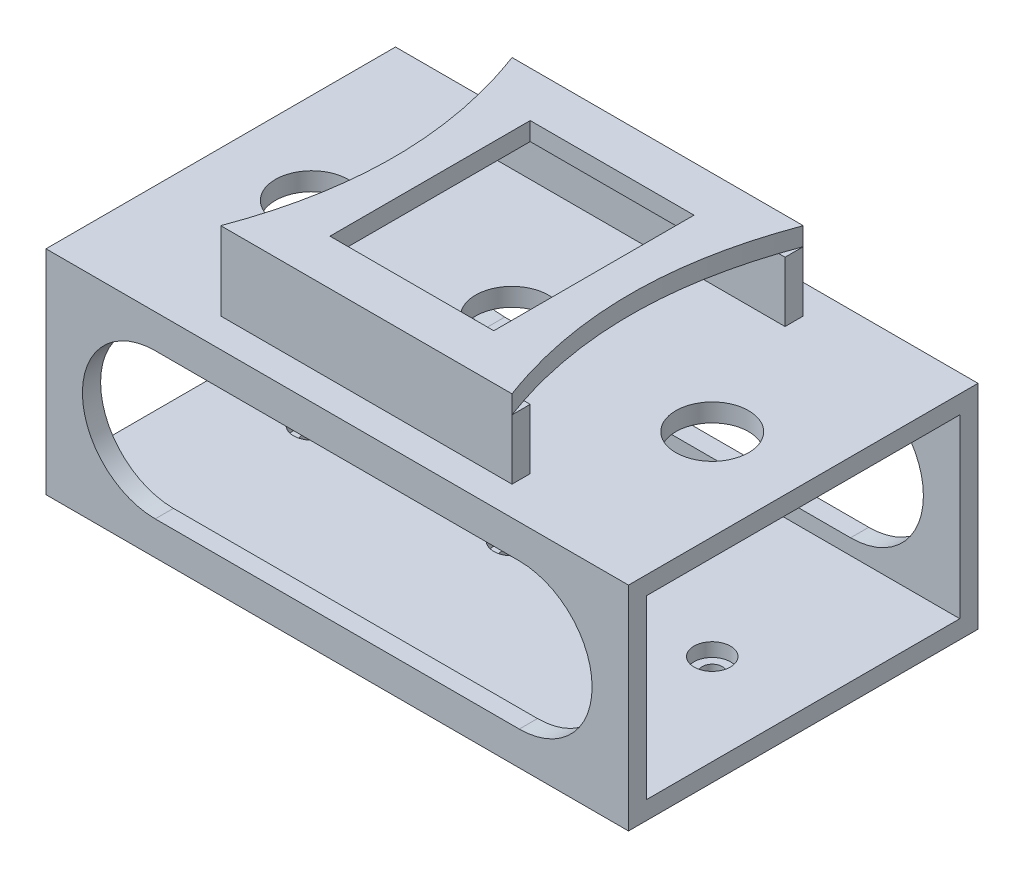
SolidWorks part; units mm, degrees
ref_plane "前视基准面" through (0, 0, 0) normal (0, 0, 1) x (1, 0, 0)
ref_plane "上视基准面" through (0, 0, 0) normal (0, 1, 0) x (1, 0, 0)
ref_plane "右视基准面" through (0, 0, 0) normal (1, 0, 0) x (0, 0, -1)
sketch "草图12" plane through (0, 0, 0) normal (0, 1, 0) x (1, 0, 0)
  line L1 (-32, 19.2) -> (32, 19.2)
  line L2 (-32, 19.2) -> (-32, -19.2)
  line L3 (-32, -19.2) -> (32, -19.2)
  line L4 (32, 19.2) -> (32, -19.2)
  line L5 (-32, 19.2) -> (32, -19.2) construction
  line L6 (-32, -19.2) -> (32, 19.2) construction
  point P0 (0, 0)
  dimension "D1" = 38.4
  dimension "D2" = 64
extrude "凸台-拉伸2" add sketch "草图12" along normal blind 23.4
sketch "草图13" plane through (32, 0, 0) normal (1, 0, 0) x (0, 0, -1)
  line L0 (-17.2, 2) -> (17.2, 2)
  line L1 (17.2, 2) -> (17.2, 21.4)
  line L2 (17.2, 21.4) -> (-17.2, 21.4)
  line L3 (-17.2, 21.4) -> (-17.2, 2)
  line L4 (-19.2, 0) -> (19.2, 0)
  line L5 (19.2, 0) -> (19.2, 23.4)
  line L6 (19.2, 23.4) -> (-19.2, 23.4)
  line L7 (-19.2, 23.4) -> (-19.2, 0)
  line L8 (-19.2, 0) -> (19.2, 0) construction
  line L9 (19.2, 0) -> (19.2, 23.4) construction
  line L10 (19.2, 23.4) -> (-19.2, 23.4) construction
  line L11 (-19.2, 23.4) -> (-19.2, 0) construction
  dimension "D1" = 0
  dimension "D2" = 2
extrude "切除-拉伸10" cut sketch "草图13" against normal through all
sketch "草图14" plane through (0, 0, 0) normal (0, -1, 0) x (1, 0, 0)
  line L0 (-32, 0) -> (-22, 0) construction
  line L1 (-32, -19.2) -> (-32, 19.2) construction
  line L2 (0, 22.2413) -> (0, -27.417) construction
  circle A0 centre (-22, 0) radius 1.1
  circle A2 centre (22, 0) radius 1.1
  circle A3 centre (-22, 0) radius 4
  circle A4 centre (22, 0) radius 4
  circle A5 centre (0, 0) radius 1.1
  circle A6 centre (0, 0) radius 4
  dimension "D1" = 2.2
  dimension "D3" = 8
  dimension "D2" = 22
extrude "凸台-拉伸3" add sketch "草图14" along normal blind 2
sketch "草图15" plane through (0, 0, 19.2) normal (0, 0, 1) x (1, 0, 0)
  line L0 (-20, 11.7) -> (20, 11.7) construction
  line L1 (-20, 19.7) -> (20, 19.7)
  line L2 (-20, 3.7) -> (20, 3.7)
  line L5 (0, 0) -> (0, 11.7) construction
  line L9 (-32, 11.7) -> (0, 11.7) construction
  line L12 (-32, 23.4) -> (-32, 0) construction
  arc A0 (-20, 19.7) -> (-20, 3.7) centre (-20, 11.7) ccw
  arc A1 (20, 3.7) -> (20, 19.7) centre (20, 11.7) ccw
  point P2 (0, 11.7)
  dimension "D2" = 8
  dimension "D1" = 40
extrude "切除-拉伸11" cut sketch "草图15" against normal through all
sketch "草图17" plane through (0, -2, 0) normal (0, -1, 0) x (1, 0, 0)
  circle A0 centre (22, 0) radius 1.1 construction
  circle A1 centre (-22, 0) radius 1.1 construction
  circle A2 centre (22, 0) radius 1.1
  circle A3 centre (-22, 0) radius 1.1
  circle A4 centre (0, 0) radius 1.1 construction
  circle A5 centre (0, 0) radius 1.1
extrude "切除-拉伸13" cut sketch "草图17" against normal up to next
sketch "草图18" plane through (0, 2, 0) normal (0, 1, 0) x (1, 0, 0)
  circle A0 centre (-22, 0) radius 2
  circle A1 centre (22, 0) radius 2
  circle A2 centre (0, 0) radius 2
  dimension "D1" = 4
extrude "切除-拉伸14" cut sketch "草图18" against normal blind 1.5
sketch "草图20" plane through (0, 23.4, 0) normal (0, 1, 0) x (1, 0, 0)
  line L1 (-16, 16) -> (16, 16)
  line L2 (-16, 16) -> (-16, -16)
  line L3 (-16, -16) -> (16, -16)
  line L4 (16, 16) -> (16, -16)
  line L5 (-16, 16) -> (16, -16) construction
  line L6 (-16, -16) -> (16, 16) construction
  point P0 (0, 0)
  dimension "D1" = 32
  dimension "D2" = 32
extrude "凸台-拉伸5" add sketch "草图20" along normal blind 8.6
sketch "草图21" plane through (16, 0, 0) normal (1, 0, 0) x (0, 0, -1)
  line L0 (-16, 32) -> (-16, 23.4) construction
  line L1 (-14, 30) -> (14, 30)
  line L2 (-14, 30) -> (-14, 23.4)
  line L3 (-14, 23.4) -> (14, 23.4)
  line L4 (14, 30) -> (14, 23.4)
  line L5 (-16, 32) -> (16, 32) construction
  dimension "D1" = 2
  dimension "D2" = 2
  dimension "D3" = 28
  dimension "D4" = 6.6
extrude "切除-拉伸16" cut sketch "草图21" against normal through all
sketch "草图23" plane through (0, 32, 0) normal (0, 1, 0) x (1, 0, 0)
  line L2 (-16, 16) -> (-16, -16) construction
  line L3 (-16, 16) -> (-16, -16)
  line L4 (-16, 0) -> (-13, 0) construction
  line L5 (0, 29.8422) -> (0, -28.5412) construction
  line L6 (16, 16) -> (16, -16)
  line L8 (-9, 11) -> (9, 11)
  line L9 (-9, 11) -> (-9, -11)
  line L10 (-9, -11) -> (9, -11)
  line L11 (9, 11) -> (9, -11)
  line L12 (-9, 11) -> (9, -11) construction
  line L13 (-9, -11) -> (9, 11) construction
  spline S0 degree 2 poles (-16, 16) (-10, 0) (-16, -16) knots 0 0 0 1 1 1
  spline S1 degree 2 poles (16, 16) (10, 0) (16, -16) knots 0 0 0 1 1 1
  point P6 (0, 0)
  dimension "D1" = 3
  dimension "D2" = 18
  dimension "D3" = 22
extrude "切除-拉伸18" cut sketch "草图23" against normal up to surface (2 mm away) up to face at (0, 30, 0)
sketch "草图22" plane through (0, 32, 0) normal (0, 1, 0) x (1, 0, 0)
  circle A0 centre (22, 0) radius 4 construction
  circle A1 centre (-22, 0) radius 4 construction
  circle A2 centre (22, 0) radius 4
  circle A3 centre (-22, 0) radius 4
  circle A4 centre (0, 0) radius 4
extrude "切除-拉伸17" cut sketch "草图22" against normal up to surface (30 mm away) up to face at (-22, 2, 2)
